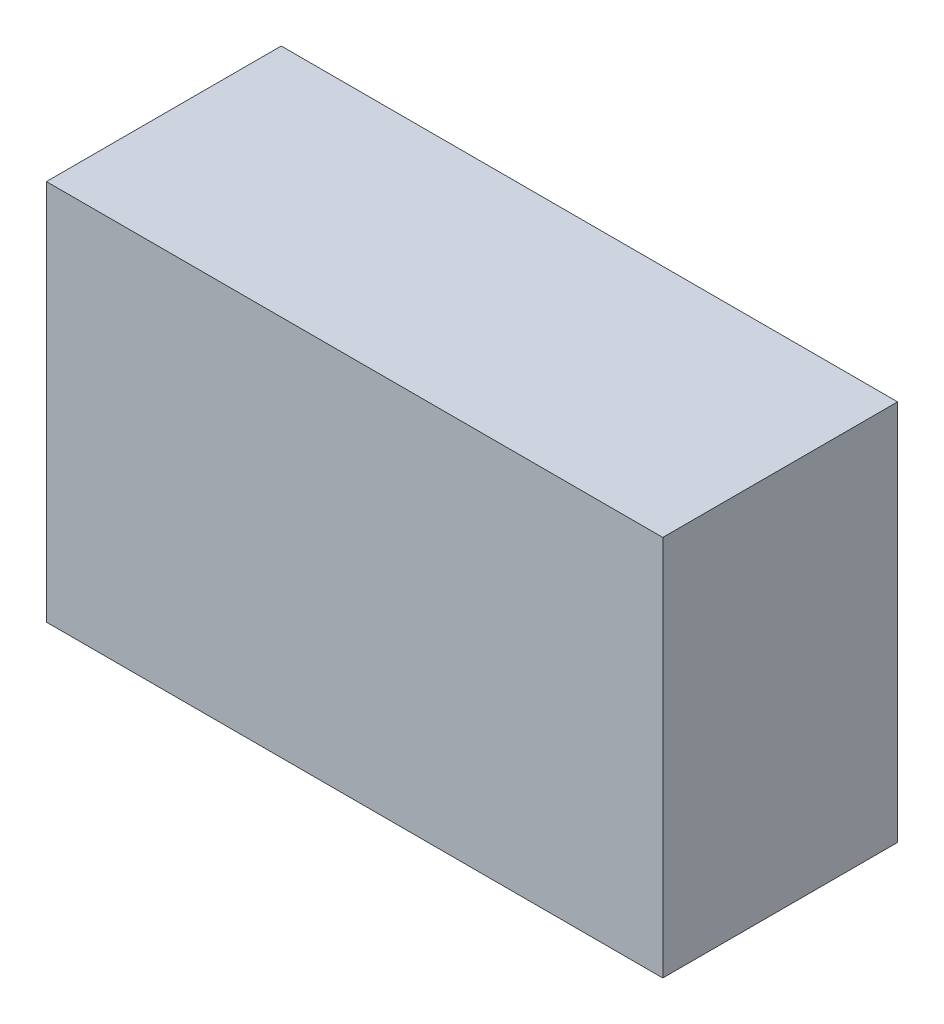
SolidWorks part; units mm, degrees
ref_plane "Front Plane" through (0, 0, 0) normal (0, 0, 1) x (1, 0, 0)
ref_plane "Top Plane" through (0, 0, 0) normal (0, 1, 0) x (1, 0, 0)
ref_plane "Right Plane" through (0, 0, 0) normal (1, 0, 0) x (0, 0, -1)
sketch "Sketch1" plane through (0, 0, 0) normal (0, 1, 0) x (1, 0, 0)
  line L1 (52.5, -20) -> (-52.5, -20)
  line L2 (52.5, -20) -> (52.5, 20)
  line L3 (52.5, 20) -> (-52.5, 20)
  line L4 (-52.5, -20) -> (-52.5, 20)
  line L5 (52.5, -20) -> (-52.5, 20) construction
  line L6 (52.5, 20) -> (-52.5, -20) construction
  point P0 (0, 0)
  dimension "D1" = 40
  dimension "D2" = 105
extrude "Boss-Extrude1" add sketch "Sketch1" along normal blind 65
